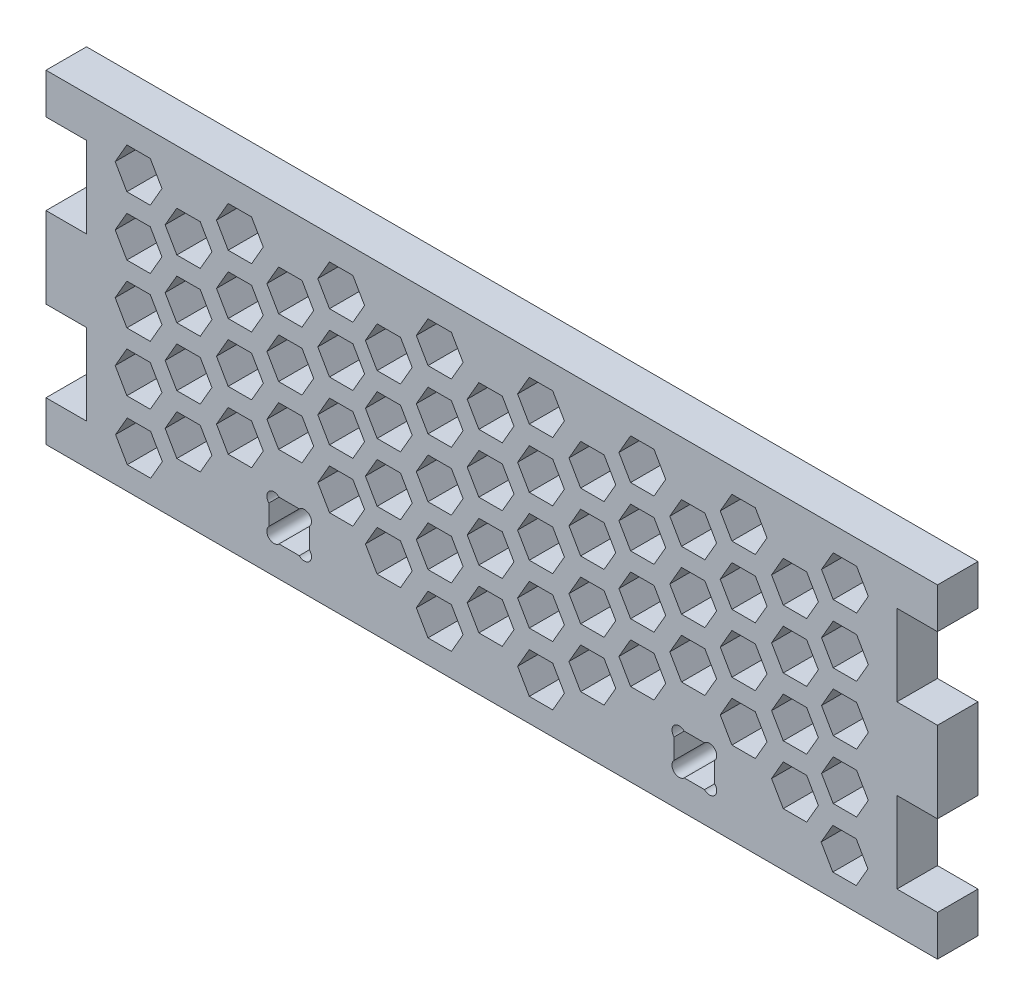
SolidWorks part; units mm, degrees
material "6061 Alloy"
ref_plane "Front" through (0, 0, 0) normal (0, 0, 1) x (1, 0, 0)
ref_plane "Top" through (0, 0, 0) normal (0, 1, 0) x (1, 0, 0)
ref_plane "Right" through (0, 0, 0) normal (1, 0, 0) x (0, 0, -1)
sketch "Sketch2" plane through (0, 0, 0) normal (0, 0, 1) x (1, 0, 0)
  line L1 (-139.7, -50.8) -> (139.7, -50.8)
  line L2 (-139.7, -50.8) -> (-139.7, 50.8)
  line L3 (-139.7, 50.8) -> (139.7, 50.8)
  line L4 (139.7, -50.8) -> (139.7, 50.8)
  line L5 (-139.7, -50.8) -> (139.7, 50.8) construction
  line L6 (-139.7, 50.8) -> (139.7, -50.8) construction
  point P0 (0, 0)
  dimension "D1" = 279.4
  dimension "D2" = 101.6
extrude "Rectangle Extrusion" add sketch "Sketch2" along normal blind 12.7
sketch "Sketch3" plane through (0, 0, 0) normal (0, 0, -1) x (-1, 0, 0)
  line L0 (-139.7, -50.8) -> (-63.5, -50.8) construction
  line L1 (139.7, -50.8) -> (-139.7, -50.8) construction
  line L2 (-63.5, -50.8) -> (-63.5, -34.925) construction
  line L3 (0, 6.985) -> (0, -6.985) construction
  line L4 (-69.85, -41.275) -> (-57.15, -41.275)
  line L5 (-69.85, -41.275) -> (-69.85, -28.575)
  line L6 (-69.85, -28.575) -> (-57.15, -28.575)
  line L7 (-57.15, -41.275) -> (-57.15, -28.575)
  line L8 (-69.85, -41.275) -> (-57.15, -28.575) construction
  line L9 (-69.85, -28.575) -> (-57.15, -41.275) construction
  line L10 (69.85, -28.575) -> (57.15, -28.575)
  line L11 (57.15, -41.275) -> (57.15, -28.575)
  line L12 (69.85, -41.275) -> (57.15, -41.275)
  line L13 (69.85, -41.275) -> (69.85, -28.575)
  line L14 (-69.85, -34.925) -> (-57.15, -34.925) construction
  circle A0 centre (-68.2625, -30.1625) radius 2.2454
  circle A1 centre (-58.7375, -30.1625) radius 2.2454
  circle A2 centre (-58.7375, -39.6875) radius 2.2454
  circle A3 centre (-68.2625, -39.6875) radius 2.2454
  circle A4 centre (58.7375, -39.6875) radius 2.2454
  circle A5 centre (68.2625, -39.6875) radius 2.2454
  circle A6 centre (58.7375, -30.1625) radius 2.2454
  circle A7 centre (68.2625, -30.1625) radius 2.2454
  dimension "D5" = 1.5875
  dimension "D6" = 4.4907
  dimension "D1" = 76.2
  dimension "D2" = 9.525
  dimension "D3" = 12.7
  dimension "D4" = 12.7
extrude "Slotting Holes" cut sketch "Sketch3" against normal up to surface (12.7 mm away) contours L6 A0 L5 | L5 A3 L4 A2 L7 A1 L6 A0 | L5 A0 L6 | A1 L7 L6 | A1 L6 L7 | L7 A2 L4 | L4 A2 L7 | A3 L5 L4 | A3 L4 L5 | L10 A6 L11 | L11 A6 L10 | L13 A7 L10 A6 L11 A4 L12 A5 | A7 L13 L10 | A7 L10 L13 | L12 A5 L13 | A4 L12 L11 | L13 A5 L12 | A4 L11 L12 up to face at (0, 0, 12.7)
sketch "Sketch4" plane through (0, 0, 12.7) normal (0, 0, 1) x (1, 0, 0)
  line L0 (0, -11.43) -> (0, 0) construction
  line L1 (6.9677, 27.5012) -> (3.3015, 33.8512)
  line L2 (-24.9281, 27.5012) -> (-28.5942, 33.8512)
  line L3 (-28.5942, 33.8512) -> (-35.9266, 33.8512)
  line L4 (-35.9266, 33.8512) -> (-39.5928, 27.5012)
  line L5 (-39.5928, 27.5012) -> (-35.9266, 21.1512)
  line L6 (-35.9266, 21.1512) -> (-28.5942, 21.1512)
  line L7 (-28.5942, 21.1512) -> (-24.9281, 27.5012)
  line L8 (3.3015, 33.8512) -> (-4.0309, 33.8512)
  line L9 (-4.0309, 33.8512) -> (-7.697, 27.5012)
  line L10 (-7.697, 27.5012) -> (-4.0309, 21.1512)
  line L11 (-4.0309, 21.1512) -> (3.3015, 21.1512)
  line L12 (3.3015, 21.1512) -> (6.9677, 27.5012)
  line L13 (38.8634, 27.5012) -> (35.1972, 33.8512)
  line L14 (35.1972, 33.8512) -> (27.8648, 33.8512)
  line L15 (27.8648, 33.8512) -> (24.1987, 27.5012)
  line L16 (24.1987, 27.5012) -> (27.8648, 21.1512)
  line L17 (27.8648, 21.1512) -> (35.1972, 21.1512)
  line L18 (35.1972, 21.1512) -> (38.8634, 27.5012)
  line L19 (-8.9802, 18.2937) -> (-12.6464, 24.6437)
  line L20 (-12.6464, 24.6437) -> (-19.9787, 24.6437)
  line L21 (-19.9787, 24.6437) -> (-23.6449, 18.2937)
  line L22 (-23.6449, 18.2937) -> (-19.9787, 11.9437)
  line L23 (-19.9787, 11.9437) -> (-12.6464, 11.9437)
  line L24 (-12.6464, 11.9437) -> (-8.9802, 18.2937)
  line L25 (22.7698, 18.2937) -> (19.1036, 24.6437)
  line L26 (19.1036, 24.6437) -> (11.7713, 24.6437)
  line L27 (11.7713, 24.6437) -> (8.1051, 18.2937)
  line L28 (8.1051, 18.2937) -> (11.7713, 11.9437)
  line L29 (11.7713, 11.9437) -> (19.1036, 11.9437)
  line L30 (19.1036, 11.9437) -> (22.7698, 18.2937)
  line L31 (-24.9281, 9.0862) -> (-28.5942, 15.4362)
  line L32 (-28.5942, 15.4362) -> (-35.9266, 15.4362)
  line L33 (-35.9266, 15.4362) -> (-39.5928, 9.0862)
  line L34 (-39.5928, 9.0862) -> (-35.9266, 2.7362)
  line L35 (-35.9266, 2.7362) -> (-28.5942, 2.7362)
  line L36 (-28.5942, 2.7362) -> (-24.9281, 9.0862)
  line L37 (6.9677, 9.0862) -> (3.3015, 15.4362)
  line L38 (3.3015, 15.4362) -> (-4.0309, 15.4362)
  line L39 (-4.0309, 15.4362) -> (-7.697, 9.0862)
  line L40 (-7.697, 9.0862) -> (-4.0309, 2.7362)
  line L41 (-4.0309, 2.7362) -> (3.3015, 2.7362)
  line L42 (3.3015, 2.7362) -> (6.9677, 9.0862)
  line L43 (38.8634, 9.0862) -> (35.1972, 15.4362)
  line L44 (35.1972, 15.4362) -> (27.8648, 15.4362)
  line L45 (27.8648, 15.4362) -> (24.1987, 9.0862)
  line L46 (24.1987, 9.0862) -> (27.8648, 2.7362)
  line L47 (27.8648, 2.7362) -> (35.1972, 2.7362)
  line L48 (35.1972, 2.7362) -> (38.8634, 9.0862)
  line L49 (-24.9281, -9.3288) -> (-28.5942, -2.9788)
  line L50 (-28.5942, -2.9788) -> (-35.9266, -2.9788)
  line L51 (-35.9266, -2.9788) -> (-39.5928, -9.3288)
  line L52 (-39.5928, -9.3288) -> (-35.9266, -15.6788)
  line L53 (-35.9266, -15.6788) -> (-28.5942, -15.6788)
  line L54 (-28.5942, -15.6788) -> (-24.9281, -9.3288)
  line L55 (-8.9802, -18.5363) -> (-12.6464, -12.1863)
  line L56 (-12.6464, -12.1863) -> (-19.9787, -12.1863)
  line L57 (-19.9787, -12.1863) -> (-23.6449, -18.5363)
  line L58 (-23.6449, -18.5363) -> (-19.9787, -24.8863)
  line L59 (-19.9787, -24.8863) -> (-12.6464, -24.8863)
  line L60 (-12.6464, -24.8863) -> (-8.9802, -18.5363)
  line L61 (6.9677, -9.3288) -> (3.3015, -2.9788)
  line L62 (3.3015, -2.9788) -> (-4.0309, -2.9788)
  line L63 (-4.0309, -2.9788) -> (-7.697, -9.3288)
  line L64 (-7.697, -9.3288) -> (-4.0309, -15.6788)
  line L65 (-4.0309, -15.6788) -> (3.3015, -15.6788)
  line L66 (3.3015, -15.6788) -> (6.9677, -9.3288)
  line L67 (22.7698, -18.5363) -> (19.1036, -12.1863)
  line L68 (19.1036, -12.1863) -> (11.7713, -12.1863)
  line L69 (11.7713, -12.1863) -> (8.1051, -18.5363)
  line L70 (8.1051, -18.5363) -> (11.7713, -24.8863)
  line L71 (11.7713, -24.8863) -> (19.1036, -24.8863)
  line L72 (19.1036, -24.8863) -> (22.7698, -18.5363)
  line L73 (38.8634, -9.3288) -> (35.1972, -2.9788)
  line L74 (35.1972, -2.9788) -> (27.8648, -2.9788)
  line L75 (27.8648, -2.9788) -> (24.1987, -9.3288)
  line L76 (24.1987, -9.3288) -> (27.8648, -15.6788)
  line L77 (27.8648, -15.6788) -> (35.1972, -15.6788)
  line L78 (35.1972, -15.6788) -> (38.8634, -9.3288)
  line L79 (38.8634, -27.7438) -> (35.1972, -21.3938)
  line L80 (35.1972, -21.3938) -> (27.8648, -21.3938)
  line L81 (27.8648, -21.3938) -> (24.1987, -27.7438)
  line L82 (24.1987, -27.7438) -> (27.8648, -34.0938)
  line L83 (27.8648, -34.0938) -> (35.1972, -34.0938)
  line L84 (35.1972, -34.0938) -> (38.8634, -27.7438)
  line L85 (6.9677, -27.7438) -> (3.3015, -21.3938)
  line L86 (-4.0309, -21.3938) -> (-7.697, -27.7438)
  line L87 (-7.697, -27.7438) -> (-4.0309, -34.0938)
  line L88 (-4.0309, -34.0938) -> (3.3015, -34.0938)
  line L89 (3.3015, -34.0938) -> (6.9677, -27.7438)
  line L90 (3.3015, -21.3938) -> (-4.0309, -21.3938)
  line L91 (-24.9281, -27.7438) -> (-28.5942, -21.3938)
  line L92 (-28.5942, -21.3938) -> (-35.9266, -21.3938)
  line L93 (-35.9266, -21.3938) -> (-39.5928, -27.7438)
  line L94 (-39.5928, -27.7438) -> (-35.9266, -34.0938)
  line L95 (-35.9266, -34.0938) -> (-28.5942, -34.0938)
  line L96 (-28.5942, -34.0938) -> (-24.9281, -27.7438)
  line L97 (22.7698, -0.1213) -> (19.1036, 6.2287)
  line L98 (19.1036, 6.2287) -> (11.7713, 6.2287)
  line L99 (11.7713, 6.2287) -> (8.1051, -0.1213)
  line L100 (8.1051, -0.1213) -> (11.7713, -6.4713)
  line L101 (11.7713, -6.4713) -> (19.1036, -6.4713)
  line L102 (19.1036, -6.4713) -> (22.7698, -0.1213)
  line L103 (-8.9802, -0.1213) -> (-12.6464, 6.2287)
  line L104 (-12.6464, 6.2287) -> (-19.9787, 6.2287)
  line L105 (-19.9787, 6.2287) -> (-23.6449, -0.1213)
  line L106 (-23.6449, -0.1213) -> (-19.9787, -6.4713)
  line L107 (-19.9787, -6.4713) -> (-12.6464, -6.4713)
  line L108 (-12.6464, -6.4713) -> (-8.9802, -0.1213)
  line L109 (-8.9802, -37.0783) -> (-12.6464, -30.7283)
  line L110 (-12.6464, -30.7283) -> (-19.9787, -30.7283)
  line L111 (-19.9787, -30.7283) -> (-23.6449, -37.0783)
  line L112 (-23.6449, -37.0783) -> (-19.9787, -43.4283)
  line L113 (-19.9787, -43.4283) -> (-12.6464, -43.4283)
  line L114 (-12.6464, -43.4283) -> (-8.9802, -37.0783)
  line L115 (22.7698, -37.0783) -> (19.1036, -30.7283)
  line L116 (19.1036, -30.7283) -> (11.7713, -30.7283)
  line L117 (11.7713, -30.7283) -> (8.1051, -37.0783)
  line L118 (8.1051, -37.0783) -> (11.7713, -43.4283)
  line L119 (11.7713, -43.4283) -> (19.1036, -43.4283)
  line L120 (19.1036, -43.4283) -> (22.7698, -37.0783)
  line L121 (-8.9802, 36.8357) -> (-12.6464, 43.1857)
  line L122 (-12.6464, 43.1857) -> (-19.9787, 43.1857)
  line L123 (-19.9787, 43.1857) -> (-23.6449, 36.8357)
  line L124 (-23.6449, 36.8357) -> (-19.9787, 30.4857)
  line L125 (-19.9787, 30.4857) -> (-12.6464, 30.4857)
  line L126 (-12.6464, 30.4857) -> (-8.9802, 36.8357)
  line L127 (22.7698, 36.8357) -> (19.1036, 43.1857)
  line L128 (19.1036, 43.1857) -> (11.7713, 43.1857)
  line L129 (11.7713, 43.1857) -> (8.1051, 36.8357)
  line L130 (8.1051, 36.8357) -> (11.7713, 30.4857)
  line L131 (11.7713, 30.4857) -> (19.1036, 30.4857)
  line L132 (19.1036, 30.4857) -> (22.7698, 36.8357)
  line L133 (63.5, -11.43) -> (63.5, 0) construction
  line L134 (70.4677, 27.5012) -> (66.8015, 33.8512)
  line L141 (66.8015, 33.8512) -> (59.4691, 33.8512)
  line L142 (59.4691, 33.8512) -> (55.803, 27.5012)
  line L143 (55.803, 27.5012) -> (59.4691, 21.1512)
  line L144 (59.4691, 21.1512) -> (66.8015, 21.1512)
  line L145 (66.8015, 21.1512) -> (70.4677, 27.5012)
  line L146 (102.3634, 27.5012) -> (98.6972, 33.8512)
  line L147 (98.6972, 33.8512) -> (91.3648, 33.8512)
  line L148 (91.3648, 33.8512) -> (87.6987, 27.5012)
  line L149 (87.6987, 27.5012) -> (91.3648, 21.1512)
  line L150 (91.3648, 21.1512) -> (98.6972, 21.1512)
  line L151 (98.6972, 21.1512) -> (102.3634, 27.5012)
  line L152 (54.5198, 18.2937) -> (50.8536, 24.6437)
  line L153 (50.8536, 24.6437) -> (43.5213, 24.6437)
  line L154 (43.5213, 24.6437) -> (39.8551, 18.2937)
  line L155 (39.8551, 18.2937) -> (43.5213, 11.9437)
  line L156 (43.5213, 11.9437) -> (50.8536, 11.9437)
  line L157 (50.8536, 11.9437) -> (54.5198, 18.2937)
  line L158 (86.2698, 18.2937) -> (82.6036, 24.6437)
  line L159 (82.6036, 24.6437) -> (75.2713, 24.6437)
  line L160 (75.2713, 24.6437) -> (71.6051, 18.2937)
  line L161 (71.6051, 18.2937) -> (75.2713, 11.9437)
  line L162 (75.2713, 11.9437) -> (82.6036, 11.9437)
  line L163 (82.6036, 11.9437) -> (86.2698, 18.2937)
  line L170 (70.4677, 9.0862) -> (66.8015, 15.4362)
  line L171 (66.8015, 15.4362) -> (59.4691, 15.4362)
  line L172 (59.4691, 15.4362) -> (55.803, 9.0862)
  line L173 (55.803, 9.0862) -> (59.4691, 2.7362)
  line L174 (59.4691, 2.7362) -> (66.8015, 2.7362)
  line L175 (66.8015, 2.7362) -> (70.4677, 9.0862)
  line L176 (102.3634, 9.0862) -> (98.6972, 15.4362)
  line L177 (98.6972, 15.4362) -> (91.3648, 15.4362)
  line L178 (91.3648, 15.4362) -> (87.6987, 9.0862)
  line L179 (87.6987, 9.0862) -> (91.3648, 2.7362)
  line L180 (91.3648, 2.7362) -> (98.6972, 2.7362)
  line L181 (98.6972, 2.7362) -> (102.3634, 9.0862)
  line L188 (54.5198, -18.5363) -> (50.8536, -12.1863)
  line L189 (50.8536, -12.1863) -> (43.5213, -12.1863)
  line L190 (43.5213, -12.1863) -> (39.8551, -18.5363)
  line L191 (39.8551, -18.5363) -> (43.5213, -24.8863)
  line L192 (43.5213, -24.8863) -> (50.8536, -24.8863)
  line L193 (50.8536, -24.8863) -> (54.5198, -18.5363)
  line L194 (70.4677, -9.3288) -> (66.8015, -2.9788)
  line L195 (66.8015, -2.9788) -> (59.4691, -2.9788)
  line L196 (59.4691, -2.9788) -> (55.803, -9.3288)
  line L197 (55.803, -9.3288) -> (59.4691, -15.6788)
  line L198 (59.4691, -15.6788) -> (66.8015, -15.6788)
  line L199 (66.8015, -15.6788) -> (70.4677, -9.3288)
  line L200 (86.2698, -18.5363) -> (82.6036, -12.1863)
  line L201 (82.6036, -12.1863) -> (75.2713, -12.1863)
  line L202 (75.2713, -12.1863) -> (71.6051, -18.5363)
  line L203 (71.6051, -18.5363) -> (75.2713, -24.8863)
  line L204 (75.2713, -24.8863) -> (82.6036, -24.8863)
  line L205 (82.6036, -24.8863) -> (86.2698, -18.5363)
  line L206 (102.3634, -9.3288) -> (98.6972, -2.9788)
  line L207 (98.6972, -2.9788) -> (91.3648, -2.9788)
  line L208 (91.3648, -2.9788) -> (87.6987, -9.3288)
  line L209 (87.6987, -9.3288) -> (91.3648, -15.6788)
  line L210 (91.3648, -15.6788) -> (98.6972, -15.6788)
  line L211 (98.6972, -15.6788) -> (102.3634, -9.3288)
  line L212 (102.3634, -27.7438) -> (98.6972, -21.3938)
  line L213 (98.6972, -21.3938) -> (91.3648, -21.3938)
  line L214 (91.3648, -21.3938) -> (87.6987, -27.7438)
  line L215 (87.6987, -27.7438) -> (91.3648, -34.0938)
  line L216 (91.3648, -34.0938) -> (98.6972, -34.0938)
  line L217 (98.6972, -34.0938) -> (102.3634, -27.7438)
  line L230 (86.2698, -0.1213) -> (82.6036, 6.2287)
  line L231 (82.6036, 6.2287) -> (75.2713, 6.2287)
  line L232 (75.2713, 6.2287) -> (71.6051, -0.1213)
  line L233 (71.6051, -0.1213) -> (75.2713, -6.4713)
  line L234 (75.2713, -6.4713) -> (82.6036, -6.4713)
  line L235 (82.6036, -6.4713) -> (86.2698, -0.1213)
  line L236 (54.5198, -0.1213) -> (50.8536, 6.2287)
  line L237 (50.8536, 6.2287) -> (43.5213, 6.2287)
  line L238 (43.5213, 6.2287) -> (39.8551, -0.1213)
  line L239 (39.8551, -0.1213) -> (43.5213, -6.4713)
  line L240 (43.5213, -6.4713) -> (50.8536, -6.4713)
  line L241 (50.8536, -6.4713) -> (54.5198, -0.1213)
  line L254 (54.5198, 36.8357) -> (50.8536, 43.1857)
  line L255 (50.8536, 43.1857) -> (43.5213, 43.1857)
  line L256 (43.5213, 43.1857) -> (39.8551, 36.8357)
  line L257 (39.8551, 36.8357) -> (43.5213, 30.4857)
  line L258 (43.5213, 30.4857) -> (50.8536, 30.4857)
  line L259 (50.8536, 30.4857) -> (54.5198, 36.8357)
  line L260 (86.2698, 36.8357) -> (82.6036, 43.1857)
  line L261 (82.6036, 43.1857) -> (75.2713, 43.1857)
  line L262 (75.2713, 43.1857) -> (71.6051, 36.8357)
  line L263 (71.6051, 36.8357) -> (75.2713, 30.4857)
  line L264 (75.2713, 30.4857) -> (82.6036, 30.4857)
  line L265 (82.6036, 30.4857) -> (86.2698, 36.8357)
  line L266 (118.0198, 36.8357) -> (114.3536, 43.1857)
  line L267 (114.3536, 43.1857) -> (107.0213, 43.1857)
  line L268 (107.0213, 43.1857) -> (103.3551, 36.8357)
  line L269 (103.3551, 36.8357) -> (107.0213, 30.4857)
  line L270 (107.0213, 30.4857) -> (114.3536, 30.4857)
  line L271 (114.3536, 30.4857) -> (118.0198, 36.8357)
  line L272 (118.0198, 18.2937) -> (114.3536, 24.6437)
  line L273 (114.3536, 24.6437) -> (107.0213, 24.6437)
  line L274 (107.0213, 24.6437) -> (103.3551, 18.2937)
  line L275 (103.3551, 18.2937) -> (107.0213, 11.9437)
  line L276 (107.0213, 11.9437) -> (114.3536, 11.9437)
  line L277 (114.3536, 11.9437) -> (118.0198, 18.2937)
  line L278 (118.0198, -0.1213) -> (114.3536, 6.2287)
  line L279 (114.3536, 6.2287) -> (107.0213, 6.2287)
  line L280 (107.0213, 6.2287) -> (103.3551, -0.1213)
  line L281 (103.3551, -0.1213) -> (107.0213, -6.4713)
  line L282 (107.0213, -6.4713) -> (114.3536, -6.4713)
  line L283 (114.3536, -6.4713) -> (118.0198, -0.1213)
  line L284 (118.0198, -18.5363) -> (114.3536, -12.1863)
  line L285 (114.3536, -12.1863) -> (107.0213, -12.1863)
  line L286 (107.0213, -12.1863) -> (103.3551, -18.5363)
  line L287 (103.3551, -18.5363) -> (107.0213, -24.8863)
  line L288 (107.0213, -24.8863) -> (114.3536, -24.8863)
  line L289 (114.3536, -24.8863) -> (118.0198, -18.5363)
  line L290 (117.8959, -37.2022) -> (114.2298, -30.8522)
  line L291 (114.2298, -30.8522) -> (106.8974, -30.8522)
  line L292 (106.8974, -30.8522) -> (103.2312, -37.2022)
  line L293 (103.2312, -37.2022) -> (106.8974, -43.5522)
  line L294 (106.8974, -43.5522) -> (114.2298, -43.5522)
  line L295 (114.2298, -43.5522) -> (117.8959, -37.2022)
  line L296 (0, -6.985) -> (0, 6.985) construction
  line L297 (-63.5, -11.43) -> (-63.5, 0) construction
  line L298 (-114.2298, -43.5522) -> (-117.8959, -37.2022)
  line L299 (-106.8974, -43.5522) -> (-114.2298, -43.5522)
  line L300 (-103.2312, -37.2022) -> (-106.8974, -43.5522)
  line L301 (-106.8974, -30.8522) -> (-103.2312, -37.2022)
  line L302 (-114.2298, -30.8522) -> (-106.8974, -30.8522)
  line L303 (-117.8959, -37.2022) -> (-114.2298, -30.8522)
  line L304 (-114.3536, -24.8863) -> (-118.0198, -18.5363)
  line L305 (-107.0213, -24.8863) -> (-114.3536, -24.8863)
  line L306 (-103.3551, -18.5363) -> (-107.0213, -24.8863)
  line L307 (-107.0213, -12.1863) -> (-103.3551, -18.5363)
  line L308 (-114.3536, -12.1863) -> (-107.0213, -12.1863)
  line L309 (-118.0198, -18.5363) -> (-114.3536, -12.1863)
  line L310 (-114.3536, -6.4713) -> (-118.0198, -0.1213)
  line L311 (-107.0213, -6.4713) -> (-114.3536, -6.4713)
  line L312 (-103.3551, -0.1213) -> (-107.0213, -6.4713)
  line L313 (-107.0213, 6.2287) -> (-103.3551, -0.1213)
  line L314 (-114.3536, 6.2287) -> (-107.0213, 6.2287)
  line L315 (-118.0198, -0.1213) -> (-114.3536, 6.2287)
  line L316 (-114.3536, 11.9437) -> (-118.0198, 18.2937)
  line L317 (-107.0213, 11.9437) -> (-114.3536, 11.9437)
  line L318 (-103.3551, 18.2937) -> (-107.0213, 11.9437)
  line L319 (-107.0213, 24.6437) -> (-103.3551, 18.2937)
  line L320 (-114.3536, 24.6437) -> (-107.0213, 24.6437)
  line L321 (-118.0198, 18.2937) -> (-114.3536, 24.6437)
  line L322 (-114.3536, 30.4857) -> (-118.0198, 36.8357)
  line L323 (-107.0213, 30.4857) -> (-114.3536, 30.4857)
  line L324 (-103.3551, 36.8357) -> (-107.0213, 30.4857)
  line L325 (-107.0213, 43.1857) -> (-103.3551, 36.8357)
  line L326 (-114.3536, 43.1857) -> (-107.0213, 43.1857)
  line L327 (-118.0198, 36.8357) -> (-114.3536, 43.1857)
  line L328 (-82.6036, 30.4857) -> (-86.2698, 36.8357)
  line L329 (-75.2713, 30.4857) -> (-82.6036, 30.4857)
  line L330 (-71.6051, 36.8357) -> (-75.2713, 30.4857)
  line L331 (-75.2713, 43.1857) -> (-71.6051, 36.8357)
  line L332 (-82.6036, 43.1857) -> (-75.2713, 43.1857)
  line L333 (-86.2698, 36.8357) -> (-82.6036, 43.1857)
  line L334 (-50.8536, 30.4857) -> (-54.5198, 36.8357)
  line L335 (-43.5213, 30.4857) -> (-50.8536, 30.4857)
  line L336 (-39.8551, 36.8357) -> (-43.5213, 30.4857)
  line L337 (-43.5213, 43.1857) -> (-39.8551, 36.8357)
  line L338 (-50.8536, 43.1857) -> (-43.5213, 43.1857)
  line L339 (-54.5198, 36.8357) -> (-50.8536, 43.1857)
  line L346 (-50.8536, -6.4713) -> (-54.5198, -0.1213)
  line L347 (-43.5213, -6.4713) -> (-50.8536, -6.4713)
  line L348 (-39.8551, -0.1213) -> (-43.5213, -6.4713)
  line L349 (-43.5213, 6.2287) -> (-39.8551, -0.1213)
  line L350 (-50.8536, 6.2287) -> (-43.5213, 6.2287)
  line L351 (-54.5198, -0.1213) -> (-50.8536, 6.2287)
  line L352 (-82.6036, -6.4713) -> (-86.2698, -0.1213)
  line L353 (-75.2713, -6.4713) -> (-82.6036, -6.4713)
  line L354 (-71.6051, -0.1213) -> (-75.2713, -6.4713)
  line L355 (-75.2713, 6.2287) -> (-71.6051, -0.1213)
  line L356 (-82.6036, 6.2287) -> (-75.2713, 6.2287)
  line L357 (-86.2698, -0.1213) -> (-82.6036, 6.2287)
  line L358 (-98.6972, -34.0938) -> (-102.3634, -27.7438)
  line L359 (-91.3648, -34.0938) -> (-98.6972, -34.0938)
  line L360 (-87.6987, -27.7438) -> (-91.3648, -34.0938)
  line L361 (-91.3648, -21.3938) -> (-87.6987, -27.7438)
  line L362 (-98.6972, -21.3938) -> (-91.3648, -21.3938)
  line L363 (-102.3634, -27.7438) -> (-98.6972, -21.3938)
  line L364 (-98.6972, -15.6788) -> (-102.3634, -9.3288)
  line L365 (-91.3648, -15.6788) -> (-98.6972, -15.6788)
  line L366 (-87.6987, -9.3288) -> (-91.3648, -15.6788)
  line L367 (-91.3648, -2.9788) -> (-87.6987, -9.3288)
  line L368 (-98.6972, -2.9788) -> (-91.3648, -2.9788)
  line L369 (-102.3634, -9.3288) -> (-98.6972, -2.9788)
  line L370 (-82.6036, -24.8863) -> (-86.2698, -18.5363)
  line L371 (-75.2713, -24.8863) -> (-82.6036, -24.8863)
  line L372 (-71.6051, -18.5363) -> (-75.2713, -24.8863)
  line L373 (-75.2713, -12.1863) -> (-71.6051, -18.5363)
  line L374 (-82.6036, -12.1863) -> (-75.2713, -12.1863)
  line L375 (-86.2698, -18.5363) -> (-82.6036, -12.1863)
  line L376 (-66.8015, -15.6788) -> (-70.4677, -9.3288)
  line L377 (-59.4691, -15.6788) -> (-66.8015, -15.6788)
  line L378 (-55.803, -9.3288) -> (-59.4691, -15.6788)
  line L379 (-59.4691, -2.9788) -> (-55.803, -9.3288)
  line L380 (-66.8015, -2.9788) -> (-59.4691, -2.9788)
  line L381 (-70.4677, -9.3288) -> (-66.8015, -2.9788)
  line L382 (-50.8536, -24.8863) -> (-54.5198, -18.5363)
  line L383 (-43.5213, -24.8863) -> (-50.8536, -24.8863)
  line L384 (-39.8551, -18.5363) -> (-43.5213, -24.8863)
  line L385 (-43.5213, -12.1863) -> (-39.8551, -18.5363)
  line L386 (-50.8536, -12.1863) -> (-43.5213, -12.1863)
  line L387 (-54.5198, -18.5363) -> (-50.8536, -12.1863)
  line L388 (-98.6972, 2.7362) -> (-102.3634, 9.0862)
  line L389 (-91.3648, 2.7362) -> (-98.6972, 2.7362)
  line L390 (-87.6987, 9.0862) -> (-91.3648, 2.7362)
  line L391 (-91.3648, 15.4362) -> (-87.6987, 9.0862)
  line L392 (-98.6972, 15.4362) -> (-91.3648, 15.4362)
  line L393 (-102.3634, 9.0862) -> (-98.6972, 15.4362)
  line L394 (-66.8015, 2.7362) -> (-70.4677, 9.0862)
  line L395 (-59.4691, 2.7362) -> (-66.8015, 2.7362)
  line L396 (-55.803, 9.0862) -> (-59.4691, 2.7362)
  line L397 (-59.4691, 15.4362) -> (-55.803, 9.0862)
  line L398 (-66.8015, 15.4362) -> (-59.4691, 15.4362)
  line L399 (-70.4677, 9.0862) -> (-66.8015, 15.4362)
  line L400 (-82.6036, 11.9437) -> (-86.2698, 18.2937)
  line L401 (-75.2713, 11.9437) -> (-82.6036, 11.9437)
  line L402 (-71.6051, 18.2937) -> (-75.2713, 11.9437)
  line L403 (-75.2713, 24.6437) -> (-71.6051, 18.2937)
  line L404 (-82.6036, 24.6437) -> (-75.2713, 24.6437)
  line L405 (-86.2698, 18.2937) -> (-82.6036, 24.6437)
  line L406 (-50.8536, 11.9437) -> (-54.5198, 18.2937)
  line L407 (-43.5213, 11.9437) -> (-50.8536, 11.9437)
  line L408 (-39.8551, 18.2937) -> (-43.5213, 11.9437)
  line L409 (-43.5213, 24.6437) -> (-39.8551, 18.2937)
  line L410 (-50.8536, 24.6437) -> (-43.5213, 24.6437)
  line L411 (-54.5198, 18.2937) -> (-50.8536, 24.6437)
  line L412 (-98.6972, 21.1512) -> (-102.3634, 27.5012)
  line L413 (-91.3648, 21.1512) -> (-98.6972, 21.1512)
  line L414 (-87.6987, 27.5012) -> (-91.3648, 21.1512)
  line L415 (-91.3648, 33.8512) -> (-87.6987, 27.5012)
  line L416 (-98.6972, 33.8512) -> (-91.3648, 33.8512)
  line L417 (-102.3634, 27.5012) -> (-98.6972, 33.8512)
  line L418 (-66.8015, 21.1512) -> (-70.4677, 27.5012)
  line L419 (-59.4691, 21.1512) -> (-66.8015, 21.1512)
  line L420 (-55.803, 27.5012) -> (-59.4691, 21.1512)
  line L421 (-59.4691, 33.8512) -> (-55.803, 27.5012)
  line L422 (-66.8015, 33.8512) -> (-59.4691, 33.8512)
  line L423 (-70.4677, 27.5012) -> (-66.8015, 33.8512)
  circle A0 centre (-32.2604, 27.5012) radius 6.35 construction
  circle A1 centre (-0.3647, 27.5012) radius 6.35 construction
  circle A2 centre (31.531, 27.5012) radius 6.35 construction
  circle A3 centre (-16.3126, 18.2937) radius 6.35 construction
  circle A4 centre (15.4374, 18.2937) radius 6.35 construction
  circle A5 centre (-32.2604, 9.0862) radius 6.35 construction
  circle A6 centre (-0.3647, 9.0862) radius 6.35 construction
  circle A7 centre (31.531, 9.0862) radius 6.35 construction
  circle A8 centre (-32.2604, -9.3288) radius 6.35 construction
  circle A9 centre (-16.3126, -18.5363) radius 6.35 construction
  circle A10 centre (-0.3647, -9.3288) radius 6.35 construction
  circle A11 centre (15.4374, -18.5363) radius 6.35 construction
  circle A12 centre (31.531, -9.3288) radius 6.35 construction
  circle A13 centre (31.531, -27.7438) radius 6.35 construction
  circle A14 centre (-0.3647, -27.7438) radius 6.35 construction
  circle A15 centre (-32.2604, -27.7438) radius 6.35 construction
  circle A16 centre (-16.3126, -0.1213) radius 6.35 construction
  circle A17 centre (15.4374, -0.1213) radius 6.35 construction
  circle A18 centre (-16.3126, -37.0783) radius 6.35 construction
  circle A19 centre (15.4374, -37.0783) radius 6.35 construction
  circle A20 centre (-16.3126, 36.8357) radius 6.35 construction
  circle A21 centre (15.4374, 36.8357) radius 6.35 construction
  circle A23 centre (63.1353, 27.5012) radius 6.35 construction
  circle A24 centre (95.031, 27.5012) radius 6.35 construction
  circle A25 centre (47.1874, 18.2937) radius 6.35 construction
  circle A26 centre (78.9374, 18.2937) radius 6.35 construction
  circle A28 centre (63.1353, 9.0862) radius 6.35 construction
  circle A29 centre (95.031, 9.0862) radius 6.35 construction
  circle A31 centre (47.1874, -18.5363) radius 6.35 construction
  circle A32 centre (63.1353, -9.3288) radius 6.35 construction
  circle A33 centre (78.9374, -18.5363) radius 6.35 construction
  circle A34 centre (95.031, -9.3288) radius 6.35 construction
  circle A35 centre (95.031, -27.7438) radius 6.35 construction
  circle A38 centre (47.1874, -0.1213) radius 6.35 construction
  circle A39 centre (78.9374, -0.1213) radius 6.35 construction
  circle A42 centre (47.1874, 36.8357) radius 6.35 construction
  circle A43 centre (78.9374, 36.8357) radius 6.35 construction
  circle A44 centre (110.6874, 36.8357) radius 6.35 construction
  circle A45 centre (110.6874, 18.2937) radius 6.35 construction
  circle A46 centre (110.6874, -0.1213) radius 6.35 construction
  circle A47 centre (110.6874, -18.5363) radius 6.35 construction
  circle A48 centre (110.6874, -37.0783) radius 6.35 construction
  circle A49 centre (-110.6874, -37.0783) radius 6.35 construction
  circle A50 centre (-110.6874, -18.5363) radius 6.35 construction
  circle A51 centre (-110.6874, -0.1213) radius 6.35 construction
  circle A52 centre (-110.6874, 18.2937) radius 6.35 construction
  circle A53 centre (-110.6874, 36.8357) radius 6.35 construction
  circle A54 centre (-78.9374, 36.8357) radius 6.35 construction
  circle A55 centre (-47.1874, 36.8357) radius 6.35 construction
  circle A57 centre (-78.9374, -0.1213) radius 6.35 construction
  circle A58 centre (-47.1874, -0.1213) radius 6.35 construction
  circle A59 centre (-95.031, -27.7438) radius 6.35 construction
  circle A60 centre (-95.031, -9.3288) radius 6.35 construction
  circle A61 centre (-78.9374, -18.5363) radius 6.35 construction
  circle A62 centre (-63.1353, -9.3288) radius 6.35 construction
  circle A63 centre (-47.1874, -18.5363) radius 6.35 construction
  circle A64 centre (-95.031, 9.0862) radius 6.35 construction
  circle A65 centre (-63.1353, 9.0862) radius 6.35 construction
  circle A66 centre (-78.9374, 18.2937) radius 6.35 construction
  circle A67 centre (-47.1874, 18.2937) radius 6.35 construction
  circle A68 centre (-95.031, 27.5012) radius 6.35 construction
  circle A69 centre (-63.1353, 27.5012) radius 6.35 construction
  dimension "D1" = 11.43
  dimension "D4" = 11.43
  dimension "D5" = 2
  dimension "D2" = 2
  dimension "D3" = 2
extrude "Honeycomb Pocketing" cut sketch "Sketch4" against normal up to surface (12.7 mm away) up to face at (-63.5, -34.925, 0)
sketch "Sketch5" plane through (0, 0, 12.7) normal (0, 0, 1) x (1, 0, 0)
  line L0 (139.7, 0) -> (139.7, 50.8) construction
  line L1 (139.7, -50.8) -> (139.7, 50.8) construction
  line L2 (139.7, 0) -> (-139.7, 0) construction
  line L3 (139.7, 25.4) -> (127, 25.4)
  line L4 (139.7, 25.4) -> (139.7, 38.1)
  line L5 (139.7, 38.1) -> (127, 38.1)
  line L6 (127, 25.4) -> (127, 38.1)
  line L7 (127, 25.4) -> (139.7, 25.4)
  line L8 (127, 25.4) -> (127, 12.7)
  line L9 (127, 12.7) -> (139.7, 12.7)
  line L10 (139.7, 25.4) -> (139.7, 12.7)
  line L11 (-139.7, 50.8) -> (-139.7, -50.8) construction
  line L12 (127, -12.7) -> (139.7, -12.7)
  line L13 (139.7, -25.4) -> (139.7, -12.7)
  line L14 (127, -25.4) -> (139.7, -25.4)
  line L15 (127, -25.4) -> (127, -12.7)
  line L16 (139.7, -38.1) -> (127, -38.1)
  line L17 (127, -25.4) -> (127, -38.1)
  line L18 (139.7, -25.4) -> (127, -25.4)
  line L19 (139.7, -25.4) -> (139.7, -38.1)
  line L20 (0, 50.8) -> (0, -50.8) construction
  line L21 (139.7, 50.8) -> (-139.7, 50.8) construction
  line L22 (-139.7, -50.8) -> (139.7, -50.8) construction
  line L23 (-139.7, -25.4) -> (-139.7, -38.1)
  line L24 (-139.7, -38.1) -> (-127, -38.1)
  line L25 (-127, -25.4) -> (-127, -38.1)
  line L26 (-127, -25.4) -> (-139.7, -25.4)
  line L27 (-139.7, -25.4) -> (-139.7, -12.7)
  line L28 (-127, -12.7) -> (-139.7, -12.7)
  line L29 (-127, -25.4) -> (-127, -12.7)
  line L30 (-139.7, 38.1) -> (-127, 38.1)
  line L31 (-127, 25.4) -> (-127, 38.1)
  line L32 (-139.7, 25.4) -> (-127, 25.4)
  line L33 (-139.7, 25.4) -> (-139.7, 38.1)
  line L34 (-127, 12.7) -> (-139.7, 12.7)
  line L35 (-139.7, 25.4) -> (-139.7, 12.7)
  line L36 (-127, 25.4) -> (-139.7, 25.4)
  line L37 (-127, 25.4) -> (-127, 12.7)
  dimension "D1" = 12.7
  dimension "D2" = 12.7
  dimension "D3" = 12.7
extrude "Cut-Extrude2" cut sketch "Sketch5" against normal blind 12.7 contours L33 L32 L31 L30 | L37 L32 L35 L34 | L26 L29 L28 L27 | L25 L26 L23 L24 | L15 L14 L13 L12 | L19 L14 L17 L16 | L6 L3 L4 L5 | L10 L3 L8 L9
